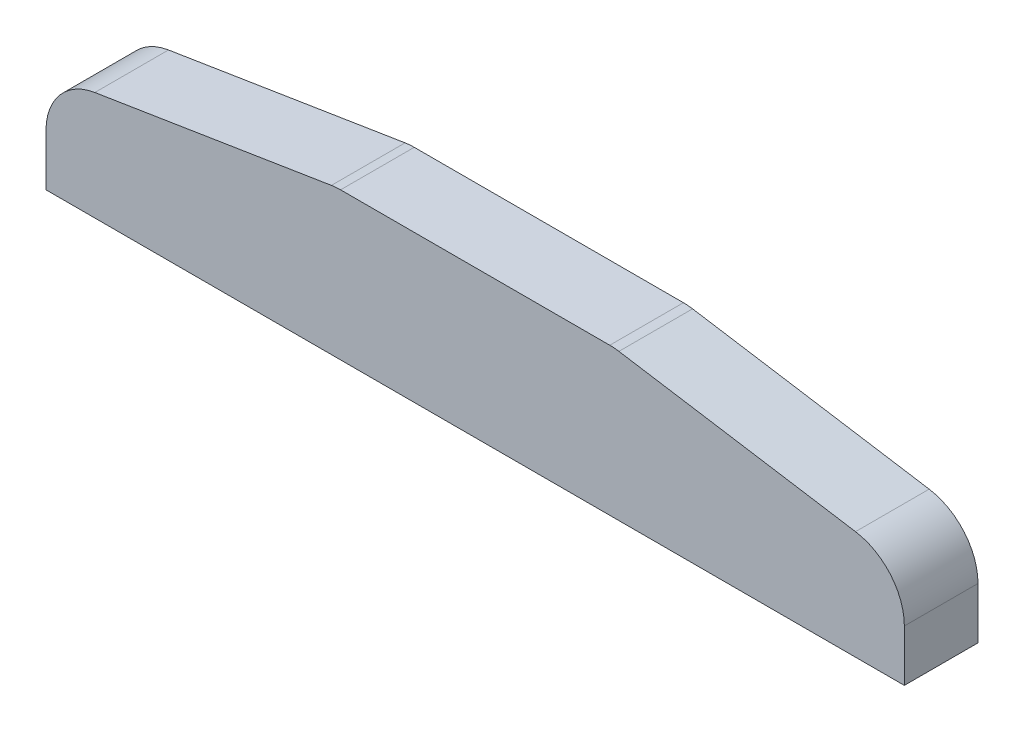
SolidWorks part; units mm, degrees
ref_plane "Front Plane" through (0, 0, 0) normal (0, 0, 1) x (1, 0, 0)
ref_plane "Top Plane" through (0, 0, 0) normal (0, 1, 0) x (1, 0, 0)
ref_plane "Right Plane" through (0, 0, 0) normal (1, 0, 0) x (0, 0, -1)
sketch "Sketch1" plane through (0, 0, 0) normal (0, 1, 0) x (1, 0, 0)
  line L1 (-74, -6.35) -> (74, -6.35)
  line L2 (-74, -6.35) -> (-74, 6.35)
  line L3 (-74, 6.35) -> (74, 6.35)
  line L4 (74, -6.35) -> (74, 6.35)
  line L5 (0, 6.35) -> (0, -6.35) construction
  line L6 (-74, 0) -> (74, 0) construction
  circle A0 centre (-66, 0) radius 2.1 construction
  circle A1 centre (-22, 0) radius 2.1 construction
  circle A2 centre (22, 0) radius 2.1 construction
  circle A3 centre (66, 0) radius 2.1 construction
  point P0 (0, 0)
  dimension "D1" = 12.7
  dimension "D2" = 4.2
  dimension "D3" = 8
  dimension "D5" = 44
  dimension "D6" = 8
  dimension "D4" = 4
extrude "Boss-Extrude1" add sketch "Sketch1" along normal blind 25.4
chamfer "Chamfer1" distance 8 distance2 50 2 edges at (74, 25.4, 0) (-74, 25.4, 0)
hole_wizard "M5x0.8 Tapped Hole1" positions "Sketch2" profile "Sketch3" tap size "M5x0.8" standard "ANSI Metric"
sketch "Sketch2" plane through (0, 0, 0) normal (0, -1, 0) x (-1, 0, 0)
  point P0 (66, 0)
  point P3 (22, 0)
  point P6 (-22, 0)
  point P9 (-66, 0)
sketch "Sketch3" plane through (-66, 0, 0) normal (1, 0, 0) x (0, 0, -1)
  line L0 (0, 0) -> (0, 13.2618)
  line L1 (0, 13.2618) -> (2.1, 12)
  line L2 (2.1, 12) -> (2.1, 0)
  line L5 (2.1, 0) -> (0, 0)
  line L10 (0, 13.2618) -> (-2.1, 12) construction
  line L11 (0, -6.35) -> (0, 107.95) construction
  dimension "Tap Drill Dia." = 4.2
  dimension "Tap Drill Depth" = 12
  dimension "Drill Angle" = 118
cosmetic thread "Hole Thread1"
cosmetic thread "Hole Thread2"
cosmetic thread "Hole Thread3"
cosmetic thread "Hole Thread4"
fillet "Fillet1" radius 10 4 edges at (74, 17.4, 0) (24, 25.4, 0) (-24, 25.4, 0) (-74, 17.4, 0)
